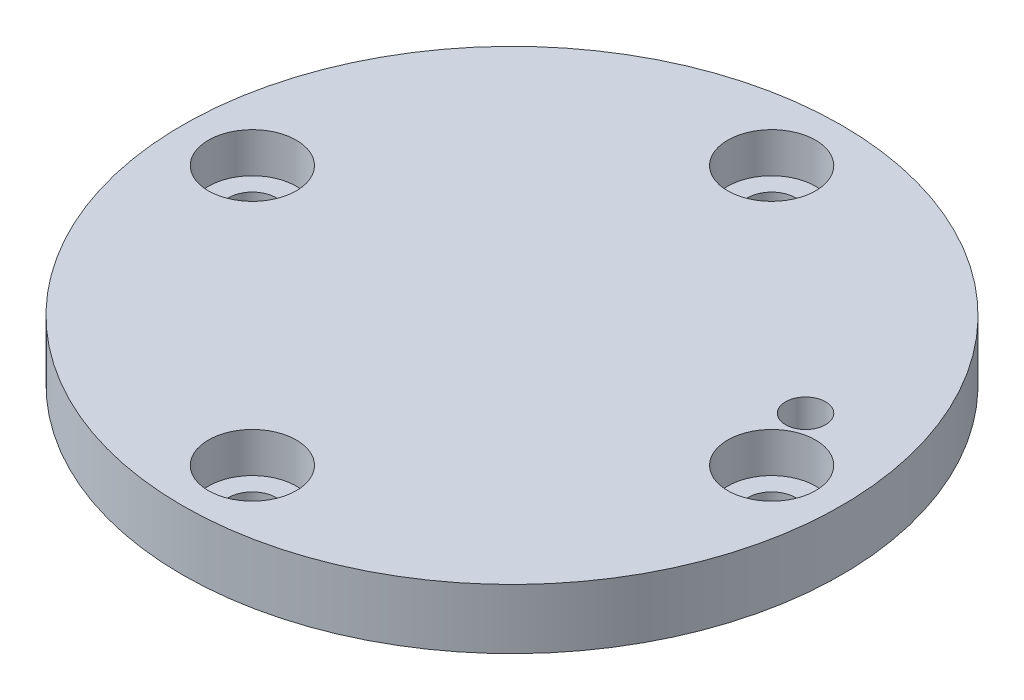
SolidWorks part; units mm, degrees
material "6061-T6 (SS)"
ref_plane "Front Plane" through (0, 0, 0) normal (0, 0, 1) x (1, 0, 0)
ref_plane "Top Plane" through (0, 0, 0) normal (0, 1, 0) x (1, 0, 0)
ref_plane "Right Plane" through (0, 0, 0) normal (1, 0, 0) x (0, 0, -1)
sketch "Sketch1" plane through (0, 0, 0) normal (0, 1, 0) x (1, 0, 0)
  circle A0 centre (0, 0) radius 16.5
  dimension "D1" = 33
extrude "Boss-Extrude1" add sketch "Sketch1" along normal blind 3
sketch "Sketch7" plane through (0, 3, 0) normal (0, 1, 0) x (1, 0, 0)
  circle A0 centre (0, -10.25) radius 0.25
  circle A1 centre (0, 0) radius 9.8
  dimension "D1" = 0.5
  dimension "D2" = 10.25
  dimension "D3" = 19.6
sketch "Sketch8" plane through (0, 3, 0) normal (0, 1, 0) x (1, 0, 0)
  line L0 (0, 0) -> (13.2071, 13.2071) construction
  circle A0 centre (7.7782, 7.7782) radius 1
  dimension "D1" = 2
  dimension "D2" = 11
sketch "Sketch9" plane through (0, 3, 0) normal (0, 1, 0) x (1, 0, 0)
  circle A0 centre (0, 0) radius 11
  dimension "D1" = 22
hole_wizard "CBORE for M2 SHCS1" positions "Sketch13" profile "Sketch14" counterbore size "M2" standard "ANSI Metric" end condition through all
sketch "Sketch13" plane through (0, 3, 0) normal (0, 1, 0) x (1, 0, 0)
  circle A0 centre (0, 0) radius 11 construction
  point P0 (-13, 0)
  dimension "D1" = 13
sketch "Sketch14" plane through (-13, 3, 0) normal (1, 0, 0) x (0, 0, 1)
  line L0 (0, 0) -> (0, 3)
  line L1 (0, 3) -> (1.2, 3)
  line L3 (1.2, 3) -> (1.2, 2)
  line L4 (1.2, 2) -> (2.2, 2)
  line L5 (2.2, 2) -> (2.2, 0)
  line L7 (2.2, 0) -> (0, 0)
  line L11 (0, -6.35) -> (0, 107.95) construction
  dimension "Thru Hole Dia." = 2.4
  dimension "Thru Hole Depth" = 3
  dimension "C'Bore Dia." = 4.4
  dimension "C'Bore Depth" = 2
pattern_circular "CirPattern1" count 4 over 360 about axis through (0, 0, 0) along (0, 1, 0) of "CBORE for M2 SHCS1"
sketch "Sketch15" plane through (0, 0, 0) normal (0, -1, 0) x (1, 0, 0)
  circle A0 centre (6, 0) radius 0.5
  dimension "D2" = 1
  dimension "D1" = 6
extrude "Cut-Extrude1" cut sketch "Sketch15" against normal blind 1.5
sketch "Sketch16" plane through (0, 3, 0) normal (0, 1, 0) x (1, 0, 0)
  line L0 (13, 0) -> (0, 0) construction
  line L1 (0, 0) -> (11.5911, 3.1058) construction
  circle A0 centre (11.5911, 3.1058) radius 1
  dimension "D1" = 2
  dimension "D2" = 12
  dimension "D3" = 15
extrude "Cut-Extrude2" cut sketch "Sketch16" against normal through all both and the other way through all
